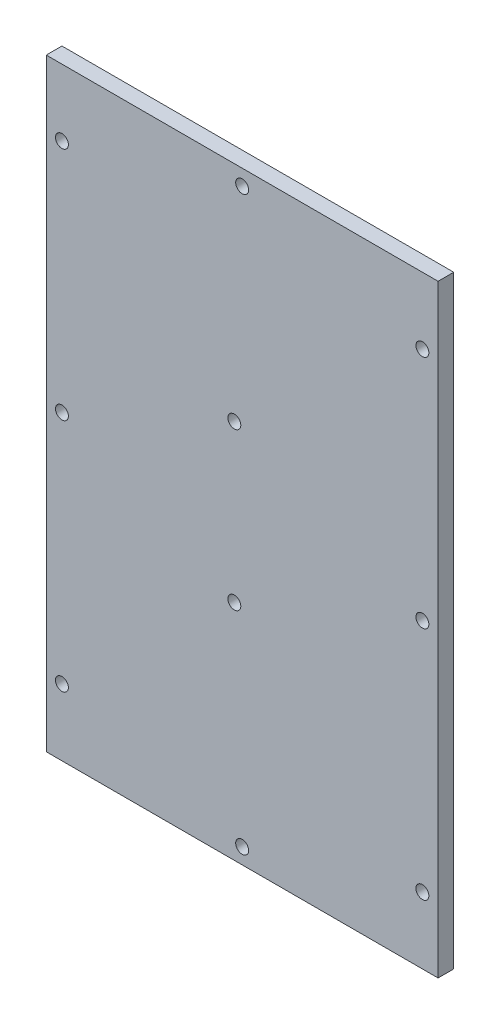
SolidWorks part; units mm, degrees
ref_plane "Front Plane" through (0, 0, 0) normal (1, 0, 0) x (0, 1, 0)
ref_plane "Top Plane" through (0, 0, 0) normal (0, 0, 1) x (0, 1, 0)
ref_plane "Right Plane" through (0, 0, 0) normal (0, 1, 0) x (-1, 0, 0)
sketch "Sketch1" plane through (0, 0, 0) normal (0, 0, 1) x (0, 1, 0)
  line L1 (0, 0) -> (154, 0)
  line L2 (0, 0) -> (0, 100)
  line L3 (0, 100) -> (154, 100)
  line L4 (154, 0) -> (154, 100)
  dimension "D1" = 154
  dimension "D2" = 100
extrude "Boss-Extrude1" add sketch "Sketch1" along normal blind 4
sketch "Sketch2" plane through (0, 0, 0) normal (0, 0, -1) x (1, 0, 0)
  line L0 (-4, 0) -> (-4, -154) construction
  line L1 (-100, 0) -> (0, 0) construction
  line L2 (0, -154) -> (-100, -154) construction
  line L3 (0, 0) -> (0, -154) construction
  line L4 (-4, -137) -> (-100, -137) construction
  line L5 (-100, -154) -> (-100, 0) construction
  line L6 (-4, -77) -> (-100, -77) construction
  line L7 (-4, -17) -> (-100, -17) construction
  line L8 (-96, 0) -> (-96, -154) construction
  line L9 (-52, -57) -> (-52, -97) construction
  circle A0 centre (-4, -77) radius 1.65
  circle A1 centre (-4, -17) radius 1.65
  circle A2 centre (-4, -137) radius 1.65
  circle A3 centre (-96, -137) radius 1.65
  circle A4 centre (-96, -77) radius 1.65
  circle A5 centre (-96, -17) radius 1.65
  circle A7 centre (-52, -97) radius 1.65
  circle A8 centre (-52, -57) radius 1.65
  circle A9 centre (-50, -4) radius 1.65
  circle A10 centre (-50, -150) radius 1.65
  point P14 (-4, -77)
  point P28 (-52, -77)
  dimension "D2" = 3.3
  dimension "D8" = 3.3
  dimension "D1" = 4
  dimension "D3" = 60
  dimension "D4" = 60
  dimension "D5" = 4
  dimension "D6" = 20
  dimension "D7" = 20
  dimension "D9" = 4
  dimension "D10" = 50
  dimension "D11" = 4
  dimension "D12" = 50
extrude "Cut-Extrude1" cut sketch "Sketch2" against normal through all
sketch "Sketch3" plane through (0, 0, 0) normal (0, 0, -1) x (1, 0, 0)
  line L0 (-85, 0) -> (-85, -153.2007) construction
  line L1 (-100, 0) -> (0, 0) construction
  line L2 (-15, 0) -> (-15, -154) construction
  line L3 (0, -154) -> (-100, -154) construction
  line L4 (-100, -139) -> (0, -139) construction
  line L5 (-100, -154) -> (-100, 0) construction
  line L6 (0, 0) -> (0, -154) construction
  line L7 (-100, -15) -> (0, -15) construction
  circle A0 centre (-85, -15) radius 7.5
  circle A1 centre (-15, -15) radius 7.5
  circle A2 centre (-15, -139) radius 7.5
  circle A3 centre (-85, -139) radius 7.5
  dimension "D5" = 15
  dimension "D1" = 15
  dimension "D2" = 15
  dimension "D3" = 15
  dimension "D4" = 15
extrude "Boss-Extrude2" add sketch "Sketch3" along normal blind 6 draft 15
sketch "Sketch4" plane through (0, 0, 0) normal (0, 0, -1) x (1, 0, 0)
  circle A0 centre (-96, -17) radius 3
  circle A1 centre (-4, -17) radius 3
  circle A2 centre (-4, -77) radius 3
  circle A3 centre (-96, -77) radius 3
  circle A4 centre (-96, -137) radius 3
  circle A5 centre (-4, -137) radius 3
  circle A6 centre (-52, -57) radius 3
  circle A8 centre (-52, -97) radius 3
  circle A9 centre (-50, -4) radius 3
  circle A10 centre (-50, -150) radius 3
  dimension "D1" = 6
extrude "Cut-Extrude2" cut sketch "Sketch4" against normal blind 1.5
